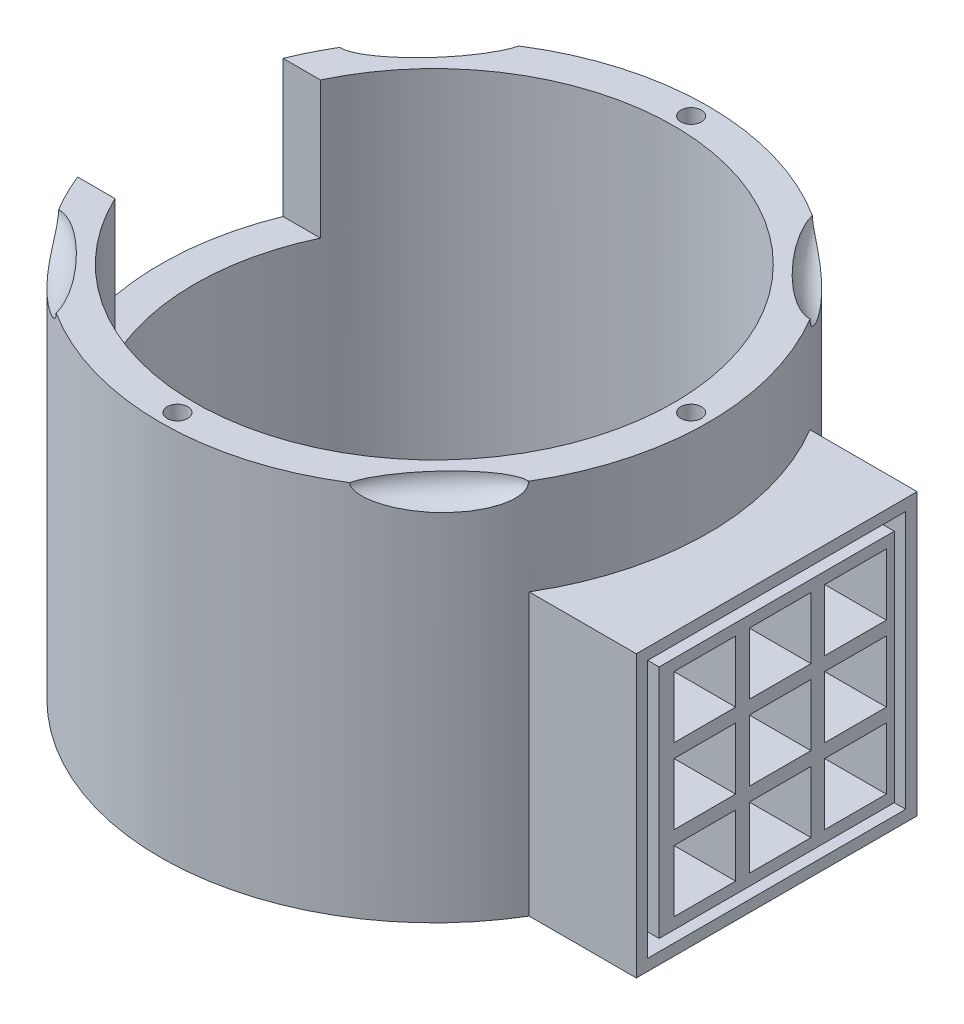
SolidWorks part; units mm, degrees
ref_plane "Front Plane" through (0, 0, 0) normal (0, 0, 1) x (1, 0, 0)
ref_plane "Top Plane" through (0, 0, 0) normal (0, 1, 0) x (1, 0, 0)
ref_plane "Right Plane" through (0, 0, 0) normal (1, 0, 0) x (0, 0, -1)
sketch "Sketch2" plane through (0, 0, 0) normal (0, 1, 0) x (1, 0, 0)
  circle A0 centre (0, 0) radius 50.8
extrude "Boss-Extrude1" add sketch "Sketch2" against normal blind 76.2
sketch "Sketch5" plane through (0, 0, 0) normal (0, 1, 0) x (1, 0, 0)
  circle A0 centre (0, 0) radius 44.45
extrude "Cut-Extrude4" cut sketch "Sketch5" against normal blind 63.5 from offset 6.35 contours A0 offset against normal yes
sketch "Sketch14" plane through (0, 0, 0) normal (0, 1, 0) x (1, 0, 0)
  circle A0 centre (0, 0) radius 7.62
extrude "Cut-Extrude6" cut sketch "Sketch14" against normal up to next
sketch "Sketch15" plane through (0, 0, 0) normal (1, 0, 0) x (0, 0, -1)
  line L1 (-19.05, -69.85) -> (20.32, -69.85)
  line L2 (-19.05, -69.85) -> (-19.05, -30.48)
  line L3 (-19.05, -30.48) -> (20.32, -30.48)
  line L4 (20.32, -69.85) -> (20.32, -30.48)
  line L5 (-50.8, 0) -> (-50.8, -76.2) construction
  line L6 (-50.8, -76.2) -> (50.8, -76.2) construction
  line L7 (-19.05, -30.48) -> (-7.62, -30.48)
  line L8 (-19.05, -30.48) -> (-19.05, -41.91)
  line L9 (-19.05, -41.91) -> (-7.62, -41.91)
  line L10 (-7.62, -30.48) -> (-7.62, -41.91)
  line L11 (-19.05, -44.45) -> (-7.62, -44.45)
  line L12 (-19.05, -44.45) -> (-19.05, -55.88)
  line L13 (-19.05, -55.88) -> (-7.62, -55.88)
  line L14 (-7.62, -44.45) -> (-7.62, -55.88)
  line L15 (-5.08, -30.48) -> (6.35, -30.48)
  line L16 (-5.08, -30.48) -> (-5.08, -41.91)
  line L17 (-5.08, -41.91) -> (6.35, -41.91)
  line L18 (6.35, -30.48) -> (6.35, -41.91)
  line L19 (-19.05, -41.91) -> (20.32, -41.91)
  line L20 (-19.05, -41.91) -> (-19.05, -44.45)
  line L21 (-19.05, -44.45) -> (20.32, -44.45)
  line L22 (20.32, -41.91) -> (20.32, -44.45)
  line L23 (-7.62, -30.48) -> (-5.08, -30.48)
  line L24 (-7.62, -30.48) -> (-7.62, -69.85)
  line L25 (-7.62, -69.85) -> (-5.08, -69.85)
  line L26 (-5.08, -30.48) -> (-5.08, -69.85)
  line L27 (6.35, -30.48) -> (8.89, -30.48)
  line L28 (6.35, -30.48) -> (6.35, -69.85)
  line L29 (6.35, -69.85) -> (8.89, -69.85)
  line L30 (8.89, -30.48) -> (8.89, -69.85)
  line L31 (-19.05, -55.88) -> (20.32, -55.88)
  line L32 (-19.05, -55.88) -> (-19.05, -58.42)
  line L33 (-19.05, -58.42) -> (20.32, -58.42)
  line L34 (20.32, -55.88) -> (20.32, -58.42)
  point P15 (-7.62, -50.165)
  dimension "D1" = 39.37
  dimension "D2" = 39.37
  dimension "D3" = 31.75
  dimension "D4" = 11.43
  dimension "D5" = 2.54
  dimension "D6" = 11.43
  dimension "D7" = 11.43
  dimension "D8" = 11.43
  dimension "D9" = 11.43
  dimension "D10" = 2.54
  dimension "D11" = 11.43
  dimension "D12" = 2.54
  dimension "D13" = 2.54
  dimension "D14" = 2.54
  dimension "D15" = 17.78
sketch "Sketch17" plane through (0, 0, 0) normal (1, 0, 0) x (0, 0, -1)
  line L0 (-50.8, -76.2) -> (50.8, -76.2) construction
  line L1 (-26.035, -76.2) -> (26.035, -76.2)
  line L2 (-26.035, -76.2) -> (-26.035, -24.13)
  line L3 (-26.035, -24.13) -> (26.035, -24.13)
  line L4 (26.035, -76.2) -> (26.035, -24.13)
  dimension "D1" = 52.07
  dimension "D2" = 52.07
  dimension "D3" = 26.035
extrude "Boss-Extrude4" add sketch "Sketch17" against normal up to surface (19.8787 mm away) from offset 63.5
extrude "Cut-Extrude7" cut sketch "Sketch15" along normal through all contours L3 L30 L19 L4 | L30 L31 L4 L21 | L33 L30 L1 L4 | L18 L3 L16 L17 | L26 L31 L28 L21 | L33 L26 L1 L28 | L33 L2 L1 L24 | L14 L11 L2 L13 | L10 L3 L2 L9
sketch "Sketch19" plane through (63.5, 0, 0) normal (1, 0, 0) x (0, 0, -1)
  line L0 (26.035, -24.13) -> (-26.035, -24.13) construction
  line L1 (-23.9183, -26.2467) -> (23.9183, -26.2467)
  line L2 (-23.9183, -26.2467) -> (-23.9183, -74.0833)
  line L3 (-23.9183, -74.0833) -> (23.9183, -74.0833)
  line L4 (23.9183, -26.2467) -> (23.9183, -74.0833)
  line L5 (-26.035, -24.13) -> (-26.035, -76.2) construction
  line L6 (26.035, -76.2) -> (26.035, -24.13) construction
  line L9 (-21.8017, -28.3633) -> (21.8017, -28.3633)
  line L10 (-21.8017, -28.3633) -> (-21.8017, -71.9667)
  line L11 (-21.8017, -71.9667) -> (21.8017, -71.9667)
  line L12 (21.8017, -28.3633) -> (21.8017, -71.9667)
  dimension "D1" = 2.1167
  dimension "D2" = 2.1167
  dimension "D3" = 2.1167
  dimension "D4" = 2.1167
  dimension "D5" = 2.1167
  dimension "D6" = 2.1167
  dimension "D7" = 2.1167
extrude "Cut-Extrude9" cut sketch "Sketch19" against normal blind 12.7
sketch "Sketch21" plane through (0, 0, 0) normal (0, 0, 1) x (1, 0, 0)
  line L0 (50.8, -24.13) -> (50.8, 0) construction
  line L1 (-50.8, 0) -> (50.8, 0)
  line L2 (-50.8, 0) -> (-50.8, -6.35)
  line L3 (-50.8, -6.35) -> (50.8, -6.35)
  line L4 (50.8, 0) -> (50.8, -6.35)
  dimension "D1" = 6.35
extrude "Cut-Extrude10" cut sketch "Sketch21" against normal through all both and the other way through all
sketch "Sketch22" plane through (0, -6.35, 0) normal (0, 1, 0) x (1, 0, 0)
  circle A0 centre (-47.625, 0) radius 1.905
  circle A1 centre (0, 0) radius 50.8 construction
  circle A2 centre (0, 47.625) radius 1.905
  circle A3 centre (47.625, 0) radius 1.905
  circle A4 centre (0, -47.625) radius 1.905
  dimension "D1" = 47.625
  dimension "D2" = 47.625
  dimension "D5" = 47.625
  dimension "D3" = 47.625
extrude "Cut-Extrude11" cut sketch "Sketch22" against normal blind 6.35
sketch "Sketch23" plane through (0, -6.35, 0) normal (0, 1, 0) x (1, 0, 0)
  line L7 (-43.5857, 26.0945) -> (-44.6594, 27.1409)
  line L8 (-27.2065, 42.9004) -> (-28.2801, 43.9468)
  line L9 (-44.6594, 27.1409) -> (-28.2801, 43.9468)
  circle A3 centre (0, 0) radius 50.8 construction
  arc A4 (-50.8, 0) -> (-35.921, 35.921) centre (0, 0) cw
  ellipse E0 centre (-35.921, 35.921) end of major axis (-44.3351, 26.4082) minor radius 3.81 (-43.5857, 26.0945) -> (-27.2065, 42.9004) ccw
revolve "Cut-Revolve2" cut sketch "Sketch23" angle 360 about L9
mirror "Mirror1" about plane through (0, 0, 0) normal (0, 0, 1) of "Cut-Revolve2"
mirror "Mirror2" about plane through (0, 0, 0) normal (1, 0, 0) of "Mirror1", "Cut-Revolve2"
sketch "Sketch24" plane through (0, 0, 0) normal (1, 0, 0) x (0, 0, -1)
  line L0 (26.0945, -6.35) -> (-26.0945, -6.35) construction
  line L1 (19.05, -6.35) -> (-19.05, -6.35)
  line L2 (19.05, -6.35) -> (19.05, -31.75)
  line L3 (19.05, -31.75) -> (-19.05, -31.75)
  line L4 (-19.05, -6.35) -> (-19.05, -31.75)
  dimension "D1" = 25.4
  dimension "D2" = 38.1
  dimension "D3" = 19.05
extrude "Cut-Extrude12" cut sketch "Sketch24" against normal up to next
